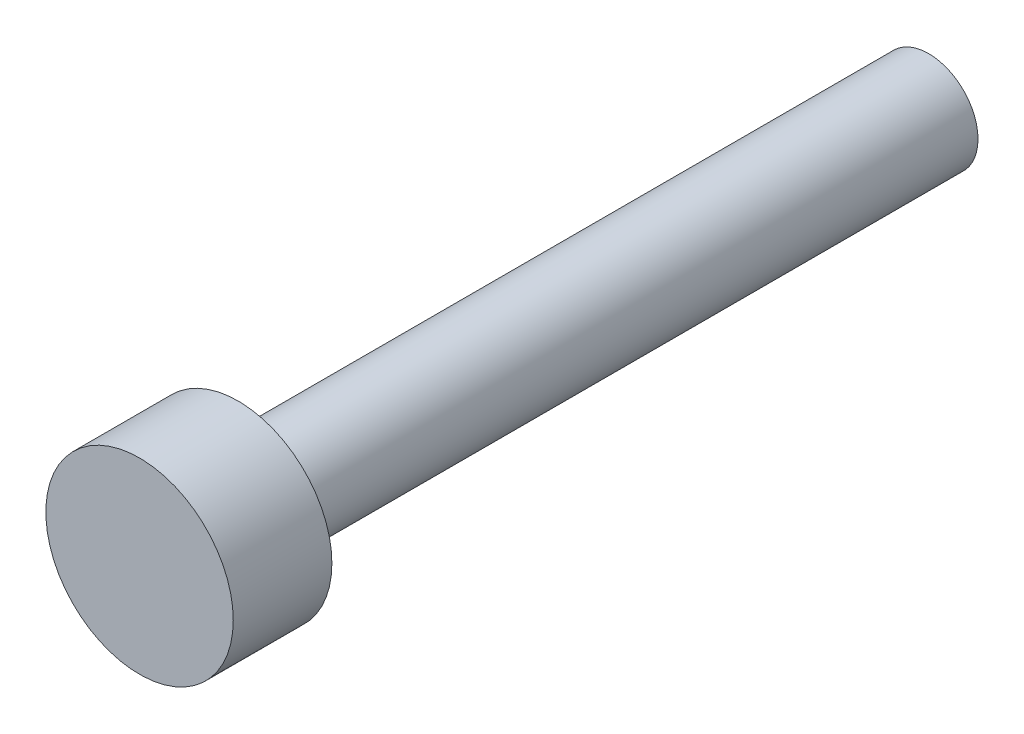
SolidWorks part; units mm, degrees
ref_plane "Front Plane" through (0, 0, 0) normal (0, 0, 1) x (1, 0, 0)
ref_plane "Top Plane" through (0, 0, 0) normal (0, 1, 0) x (1, 0, 0)
ref_plane "Right Plane" through (0, 0, 0) normal (1, 0, 0) x (0, 0, -1)
sketch "Sketch1" plane through (0, 0, 0) normal (0, 0, 1) x (1, 0, 0)
  circle A0 centre (0, 0) radius 1
extrude "Thread_Envelope" add sketch "Sketch1" along normal blind 14 from offset 14
sketch "Sketch2" plane through (0, 0, 0) normal (0, 0, 1) x (1, 0, 0)
  circle A0 centre (0, 0) radius 1.9
extrude "Head_Envelope" add sketch "Sketch2" along normal blind 2
